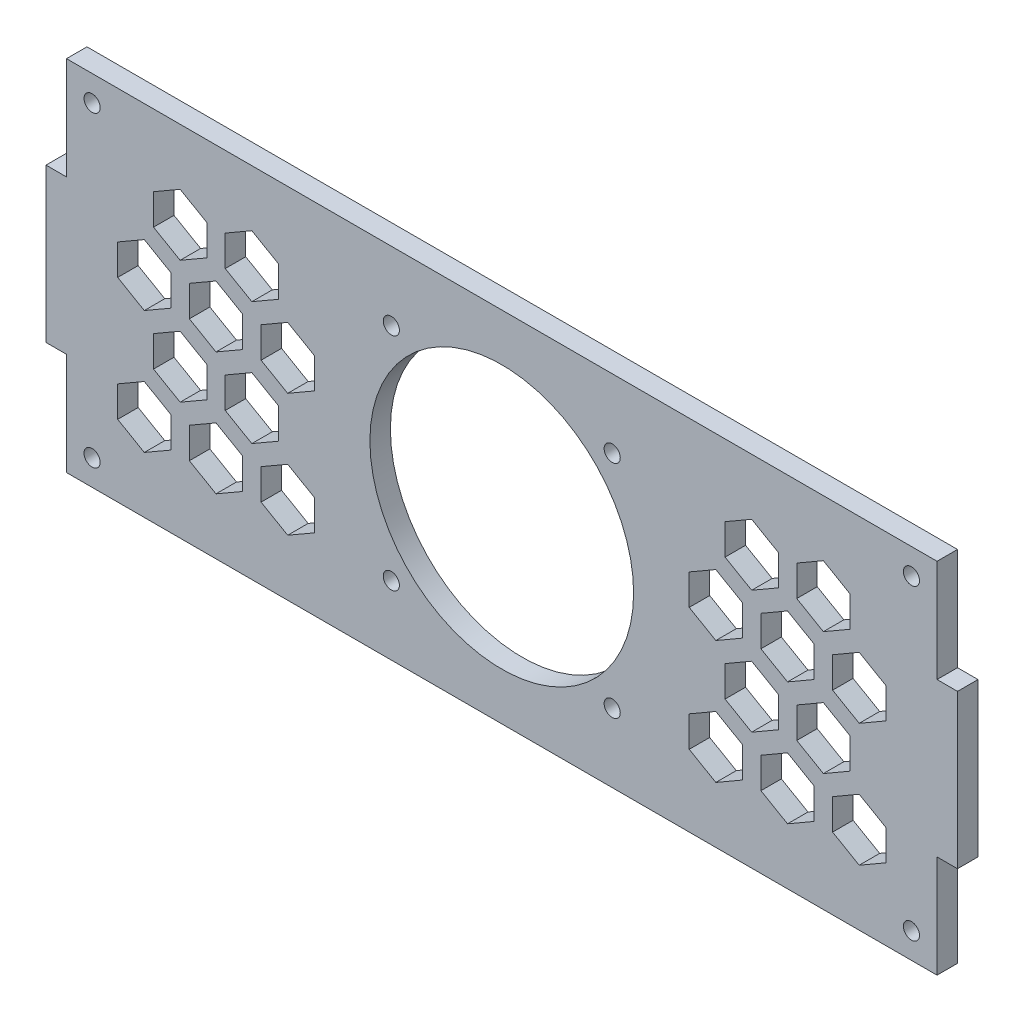
SolidWorks part; units mm, degrees
ref_plane "前视基准面" through (0, 0, 0) normal (0, 0, 1) x (1, 0, 0)
ref_plane "上视基准面" through (0, 0, 0) normal (0, 1, 0) x (1, 0, 0)
ref_plane "右视基准面" through (0, 0, 0) normal (1, 0, 0) x (0, 0, -1)
other "Configuration Table"
sketch "草图1" plane through (0, 0, 0) normal (0, 0, 1) x (1, 0, 0)
  line L1 (0, 0) -> (178, 0)
  line L2 (0, 0) -> (0, -70)
  line L3 (0, -70) -> (178, -70)
  line L4 (178, 0) -> (178, -70)
  dimension "D1" = 178
  dimension "D2" = 70
extrude "凸台-拉伸1" add sketch "草图1" along normal blind 4
sketch "草图2" plane through (0, 0, 4) normal (0, 0, 1) x (1, 0, 0)
  line L0 (89, -35) -> (89, 0) construction
  line L1 (178, 0) -> (0, 0) construction
  line L2 (0, -35) -> (89, -35) construction
  line L3 (0, 0) -> (0, -70) construction
  line L4 (39, -35) -> (39, 0) construction
  line L5 (4, 0) -> (4, -20)
  line L6 (178, 0) -> (174, 0)
  line L7 (178, 0) -> (178, -20)
  line L8 (178, -20) -> (174, -20)
  line L9 (174, 0) -> (174, -20)
  line L14 (0, -20) -> (4, -20)
  line L15 (0, 0) -> (0, -20)
  line L16 (0, 0) -> (4, 0)
  line L17 (174, -70) -> (174, -50)
  line L18 (178, -50) -> (174, -50)
  line L19 (178, -70) -> (178, -50)
  line L20 (178, -70) -> (174, -70)
  line L21 (0, -70) -> (4, -70)
  line L22 (0, -70) -> (0, -50)
  line L23 (0, -50) -> (4, -50)
  line L24 (4, -70) -> (4, -50)
  line L25 (89, -35) -> (67.4332, -13.4332) construction
  line L26 (40.1962, -11) -> (35, -14)
  line L27 (26.1962, -23) -> (31.3923, -20)
  line L28 (31.3923, -20) -> (31.3923, -14)
  line L29 (31.3923, -14) -> (26.1962, -11)
  line L30 (26.1962, -11) -> (21, -14)
  line L31 (21, -14) -> (21, -20)
  line L32 (21, -20) -> (26.1962, -23)
  line L33 (45.3923, -14) -> (40.1962, -11)
  line L34 (35, -14) -> (35, -20)
  line L35 (35, -20) -> (40.1962, -23)
  line L36 (40.1962, -23) -> (45.3923, -20)
  line L37 (45.3923, -20) -> (45.3923, -14)
  line L44 (33.1962, -23) -> (33.1962, -35) construction
  line L45 (33.1962, -35) -> (38.3923, -32)
  line L46 (38.3923, -32) -> (38.3923, -26)
  line L47 (38.3923, -26) -> (33.1962, -23)
  line L48 (33.1962, -23) -> (28, -26)
  line L49 (28, -26) -> (28, -32)
  line L50 (28, -32) -> (33.1962, -35)
  line L51 (52.3923, -26) -> (47.1962, -23)
  line L52 (52.3923, -32) -> (52.3923, -26)
  line L53 (47.1962, -35) -> (52.3923, -32)
  line L54 (42, -32) -> (47.1962, -35)
  line L55 (47.1962, -23) -> (42, -26)
  line L56 (42, -26) -> (42, -32)
  line L57 (24.3923, -26) -> (24.3923, -32)
  line L58 (19.1962, -23) -> (24.3923, -26)
  line L59 (24.3923, -32) -> (19.1962, -35)
  line L60 (19.1962, -35) -> (14, -32)
  line L61 (14, -32) -> (14, -26)
  line L62 (14, -26) -> (19.1962, -23)
  line L63 (14, -29) -> (52.3923, -29) construction
  line L70 (45.3923, -38) -> (45.3923, -44)
  line L71 (40.1962, -35) -> (45.3923, -38)
  line L72 (35, -38) -> (40.1962, -35)
  line L73 (35, -44) -> (35, -38)
  line L74 (45.3923, -44) -> (40.1962, -47)
  line L75 (21, -38) -> (26.1962, -35)
  line L76 (21, -44) -> (21, -38)
  line L77 (26.1962, -47) -> (21, -44)
  line L78 (31.3923, -44) -> (26.1962, -47)
  line L79 (31.3923, -38) -> (31.3923, -44)
  line L80 (26.1962, -35) -> (31.3923, -38)
  line L81 (40.1962, -47) -> (35, -44)
  line L82 (21, -41) -> (45.3923, -41) construction
  line L83 (14, -53) -> (52.3923, -53) construction
  line L84 (33.1962, -59) -> (33.1962, -47) construction
  line L85 (14, -56) -> (19.1962, -59)
  line L86 (14, -50) -> (14, -56)
  line L87 (19.1962, -47) -> (14, -50)
  line L88 (24.3923, -50) -> (19.1962, -47)
  line L89 (19.1962, -59) -> (24.3923, -56)
  line L90 (24.3923, -56) -> (24.3923, -50)
  line L91 (42, -56) -> (42, -50)
  line L92 (47.1962, -59) -> (42, -56)
  line L93 (42, -50) -> (47.1962, -47)
  line L94 (47.1962, -47) -> (52.3923, -50)
  line L95 (52.3923, -50) -> (52.3923, -56)
  line L96 (52.3923, -56) -> (47.1962, -59)
  line L97 (28, -50) -> (33.1962, -47)
  line L98 (28, -56) -> (28, -50)
  line L99 (33.1962, -59) -> (28, -56)
  line L100 (38.3923, -56) -> (33.1962, -59)
  line L101 (38.3923, -50) -> (38.3923, -56)
  line L102 (33.1962, -47) -> (38.3923, -50)
  line L103 (144.8038, -59) -> (144.8038, -47) construction
  line L104 (164, -53) -> (125.6077, -53) construction
  line L105 (157, -41) -> (132.6077, -41) construction
  line L106 (164, -29) -> (125.6077, -29) construction
  line L107 (144.8038, -23) -> (144.8038, -35) construction
  line L108 (144.8038, -47) -> (139.6077, -50)
  line L109 (139.6077, -50) -> (139.6077, -56)
  line L110 (139.6077, -56) -> (144.8038, -59)
  line L111 (144.8038, -59) -> (150, -56)
  line L112 (150, -56) -> (150, -50)
  line L113 (150, -50) -> (144.8038, -47)
  line L114 (125.6077, -56) -> (130.8038, -59)
  line L115 (125.6077, -50) -> (125.6077, -56)
  line L116 (130.8038, -47) -> (125.6077, -50)
  line L117 (136, -50) -> (130.8038, -47)
  line L118 (130.8038, -59) -> (136, -56)
  line L119 (136, -56) -> (136, -50)
  line L120 (153.6077, -56) -> (153.6077, -50)
  line L121 (158.8038, -59) -> (153.6077, -56)
  line L122 (153.6077, -50) -> (158.8038, -47)
  line L123 (158.8038, -47) -> (164, -50)
  line L124 (164, -50) -> (164, -56)
  line L125 (164, -56) -> (158.8038, -59)
  line L126 (137.8038, -47) -> (143, -44)
  line L127 (151.8038, -35) -> (146.6077, -38)
  line L128 (146.6077, -38) -> (146.6077, -44)
  line L129 (146.6077, -44) -> (151.8038, -47)
  line L130 (151.8038, -47) -> (157, -44)
  line L131 (157, -44) -> (157, -38)
  line L132 (157, -38) -> (151.8038, -35)
  line L133 (132.6077, -44) -> (137.8038, -47)
  line L134 (143, -44) -> (143, -38)
  line L135 (143, -38) -> (137.8038, -35)
  line L136 (137.8038, -35) -> (132.6077, -38)
  line L137 (132.6077, -38) -> (132.6077, -44)
  line L144 (164, -26) -> (158.8038, -23)
  line L145 (164, -32) -> (164, -26)
  line L146 (158.8038, -35) -> (164, -32)
  line L147 (153.6077, -32) -> (158.8038, -35)
  line L148 (158.8038, -23) -> (153.6077, -26)
  line L149 (153.6077, -26) -> (153.6077, -32)
  line L150 (136, -26) -> (136, -32)
  line L151 (130.8038, -23) -> (136, -26)
  line L152 (136, -32) -> (130.8038, -35)
  line L153 (130.8038, -35) -> (125.6077, -32)
  line L154 (125.6077, -32) -> (125.6077, -26)
  line L155 (125.6077, -26) -> (130.8038, -23)
  line L156 (150, -32) -> (144.8038, -35)
  line L157 (150, -26) -> (150, -32)
  line L158 (144.8038, -23) -> (150, -26)
  line L159 (139.6077, -26) -> (144.8038, -23)
  line L160 (139.6077, -32) -> (139.6077, -26)
  line L161 (144.8038, -35) -> (139.6077, -32)
  line L168 (132.6077, -20) -> (132.6077, -14)
  line L169 (137.8038, -23) -> (132.6077, -20)
  line L170 (143, -20) -> (137.8038, -23)
  line L171 (143, -14) -> (143, -20)
  line L172 (132.6077, -14) -> (137.8038, -11)
  line L173 (157, -20) -> (151.8038, -23)
  line L174 (157, -14) -> (157, -20)
  line L175 (151.8038, -11) -> (157, -14)
  line L176 (146.6077, -14) -> (151.8038, -11)
  line L177 (146.6077, -20) -> (146.6077, -14)
  line L178 (151.8038, -23) -> (146.6077, -20)
  line L179 (137.8038, -11) -> (143, -14)
  line L180 (54.1962, -11) -> (49, -14) [skipped]
  line L181 (59.3923, -14) -> (54.1962, -11) [skipped]
  line L182 (49, -14) -> (49, -20) [skipped]
  line L183 (49, -20) -> (54.1962, -23) [skipped]
  line L184 (54.1962, -23) -> (59.3923, -20) [skipped]
  line L185 (59.3923, -20) -> (59.3923, -14) [skipped]
  circle A0 centre (89, -35) radius 25.75
  circle A13 centre (9, -5) radius 1.575
  circle A14 centre (9, -65) radius 1.575
  circle A15 centre (169, -65) radius 1.575
  circle A16 centre (169, -5) radius 1.575
  circle A17 centre (67.4332, -13.4332) radius 1.575
  circle A18 centre (110.5668, -13.4332) radius 1.575
  circle A19 centre (110.5668, -56.5668) radius 1.575
  circle A20 centre (67.4332, -56.5668) radius 1.575
  circle A21 centre (26.1962, -17) radius 5.1962 construction
  circle A22 centre (33.1962, -29) radius 5.1962 construction
  circle A23 centre (47.1962, -29) radius 5.1962 construction
  circle A24 centre (19.1962, -29) radius 5.1962 construction
  circle A25 centre (26.1962, -41) radius 5.1962 construction
  circle A26 centre (19.1962, -53) radius 5.1962 construction
  circle A27 centre (47.1962, -53) radius 5.1962 construction
  circle A28 centre (33.1962, -53) radius 5.1962 construction
  circle A29 centre (144.8038, -53) radius 5.1962 construction
  circle A30 centre (130.8038, -53) radius 5.1962 construction
  circle A31 centre (158.8038, -53) radius 5.1962 construction
  circle A32 centre (151.8038, -41) radius 5.1962 construction
  circle A33 centre (158.8038, -29) radius 5.1962 construction
  circle A34 centre (130.8038, -29) radius 5.1962 construction
  circle A35 centre (144.8038, -29) radius 5.1962 construction
  circle A36 centre (151.8038, -17) radius 5.1962 construction
  point P19 (89, -35)
  point P22 (89, -35)
  point P60 (61.8696, -45.6208)
  point P61 (47.1962, -35)
  point P62 (45.3923, -41)
  point P139 (0, 0)
  dimension "D1" = 51.5
  dimension "D3" = 3.15
  dimension "D5" = 4
  dimension "D11" = 3.15
  dimension "D2" = 30.5
  dimension "D6" = 6
  dimension "D7" = 50
  dimension "D8" = 11
  dimension "D9" = 4
  dimension "D10" = 20
  dimension "D12" = 5
  dimension "D13" = 5
  dimension "D4" = 45
  dimension "D14" = 17
  dimension "D16" = 3.6077
  dimension "D17" = 6
  dimension "D18" = 3
  dimension "D20" = 3.6077
  dimension "D15" = 3
  dimension "D19" = 2
extrude "切除-拉伸1" cut sketch "草图2" against normal through all
